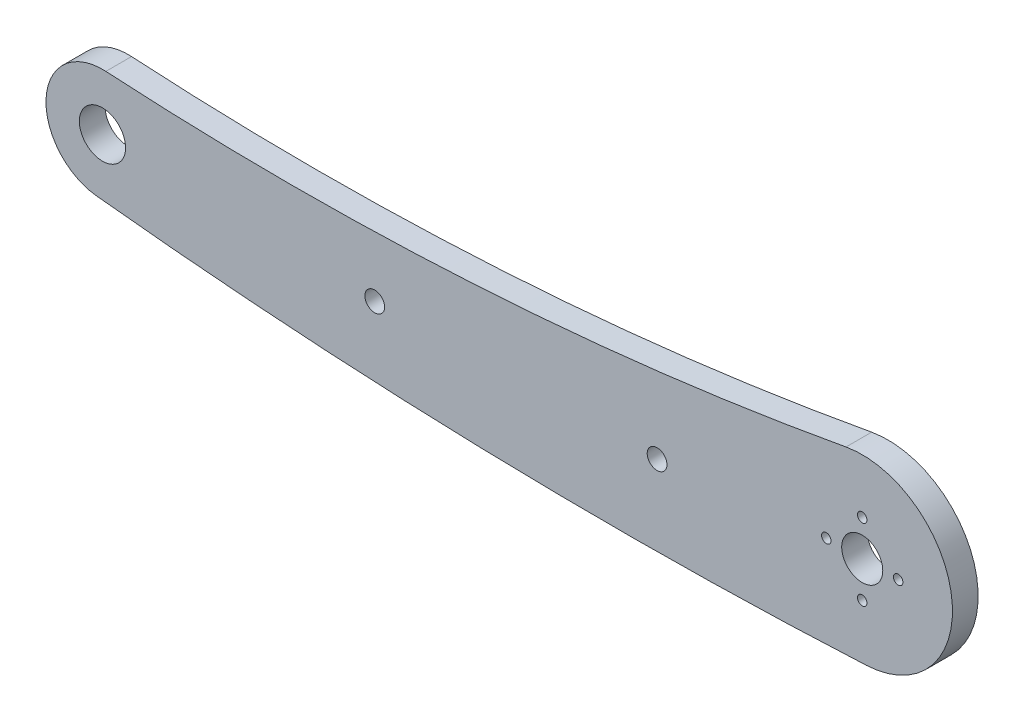
SolidWorks part; units mm, degrees
ref_plane "Plan de face" through (0, 0, 0) normal (0, 0, 1) x (1, 0, 0)
ref_plane "Plan de dessus" through (0, 0, 0) normal (0, 1, 0) x (1, 0, 0)
ref_plane "Plan de droite" through (0, 0, 0) normal (1, 0, 0) x (0, 0, -1)
sketch "Esquisse1" plane through (0, 0, 0) normal (0, 0, 1) x (1, 0, 0)
  circle A0 centre (30.768, -3.8266) radius 1.925
  circle A1 centre (-24.2246, -4.724) radius 1.925
  circle A2 centre (70.7219, -0.6743) radius 7 construction
  arc A3 (-76.5965, 7.891) -> (-78.4339, -14.026) centre (-77.2584, -3.089) ccw
  arc A4 (-76.5965, 7.891) -> (67.5569, 16.6134) centre (-40.4946, 606.8039) ccw
  arc A5 (71.6197, -18.2263) -> (67.5569, 16.6134) centre (70.7219, -0.6743) ccw
  circle A6 centre (77.7219, -0.6743) radius 0.925
  arc A7 (69.3878, -18.3379) -> (71.6197, -18.2263) centre (23.0916, 930.5334) ccw
  arc A8 (-78.4339, -14.026) -> (69.3878, -18.3379) centre (23.0916, 930.5334) ccw
  circle A9 centre (70.7219, -7.6743) radius 0.925
  circle A10 centre (63.7219, -0.6743) radius 0.925
  circle A11 centre (70.7219, 6.3257) radius 0.925
  circle A13 centre (70.7219, -0.6743) radius 4
  circle A14 centre (-77.2584, -3.089) radius 4.5
  point P23 (70.7219, -0.6743)
  dimension "D1" = 600
  dimension "D2" = 950
  dimension "D3" = 11
  dimension "D4" = 17.575
  dimension "D5" = 8
  dimension "D6" = 9
  dimension "D7" = 3.85
  dimension "D8" = 3.85
  dimension "D9" = 14
  dimension "D10" = 1.85
  dimension "D11" = 4
extrude "Boss.-Extru.1" add sketch "Esquisse1" along normal blind 5
